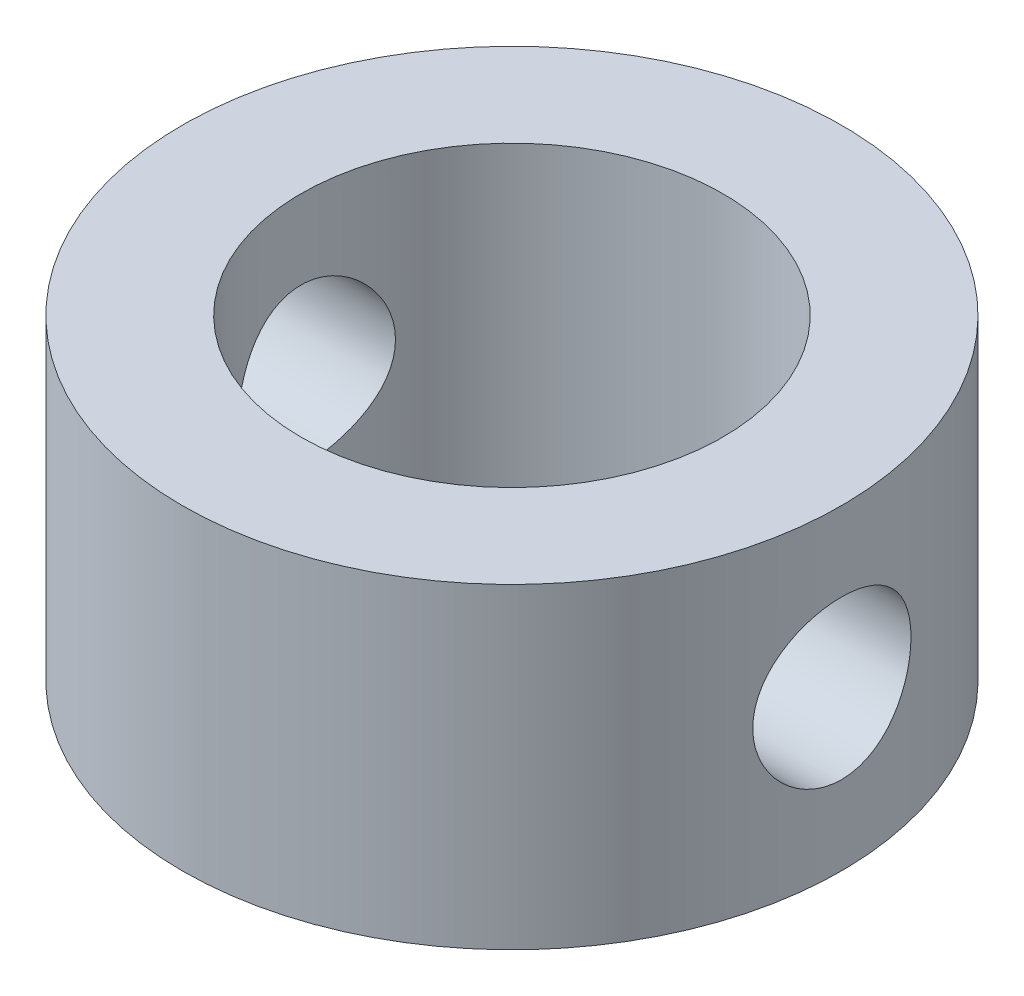
SolidWorks part; units mm, degrees
ref_plane "Front Plane" through (0, 0, 0) normal (0, 0, 1) x (1, 0, 0)
ref_plane "Top Plane" through (0, 0, 0) normal (0, 1, 0) x (1, 0, 0)
ref_plane "Right Plane" through (0, 0, 0) normal (1, 0, 0) x (0, 0, -1)
sketch "Sketch1" plane through (0, 0, 0) normal (0, 1, 0) x (1, 0, 0)
  circle A0 centre (0, 0) radius 12.5
  circle A1 centre (0, 0) radius 8
  dimension "D1" = 25
  dimension "D2" = 16
extrude "Boss-Extrude1" add sketch "Sketch1" along normal blind 12
sketch "Sketch2" plane through (0, 0, 0) normal (1, 0, 0) x (0, 0, -1)
  line L0 (12.5, 12) -> (-12.5, 12) construction
  circle A0 centre (0, 6) radius 3
  dimension "D1" = 6
  dimension "D2" = 6
extrude "Cut-Extrude1" cut sketch "Sketch2" against normal mid plane 48
